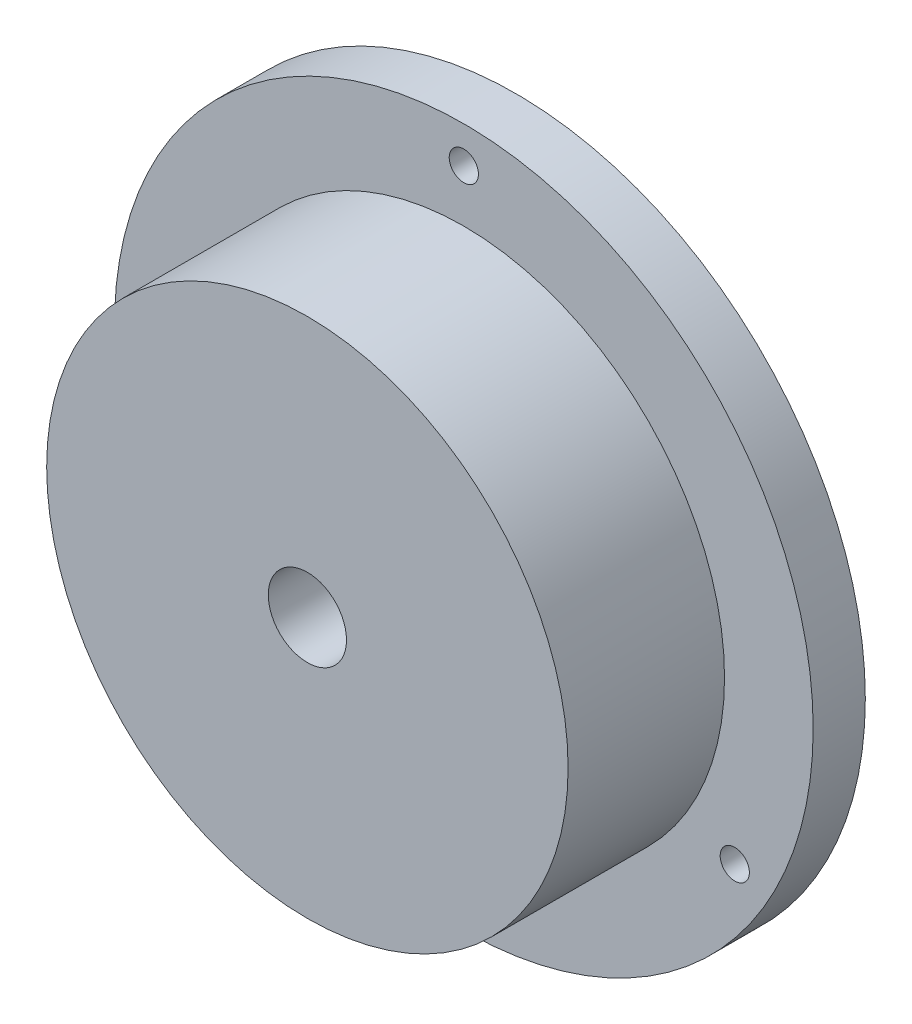
SolidWorks part; units mm, degrees
ref_plane "Front Plane" through (0, 0, 0) normal (0, 0, 1) x (1, 0, 0)
ref_plane "Top Plane" through (0, 0, 0) normal (0, 1, 0) x (1, 0, 0)
ref_plane "Right Plane" through (0, 0, 0) normal (1, 0, 0) x (0, 0, -1)
sketch "Sketch1" plane through (0, 0, 0) normal (0, 0, 1) x (1, 0, 0)
  circle A0 centre (0, 0) radius 21.2725
  dimension "D1" = 42.545
extrude "Boss-Extrude1" add sketch "Sketch1" along normal blind 3.175
sketch "Sketch2" plane through (0, 0, 3.175) normal (0, 0, 1) x (1, 0, 0)
  circle A0 centre (0, 0) radius 15.875
  dimension "D1" = 31.75
extrude "Boss-Extrude2" add sketch "Sketch2" along normal blind 9.525
hole_wizard "3/16 (0.1875) Diameter Hole1" positions "Sketch4" profile "Sketch3" hole size "3/16" standard "Ansi Inch" end condition through all
sketch "Sketch4" plane through (0, 0, 12.7) normal (0, 0, 1) x (1, 0, 0)
  point P1 (0, 0)
sketch "Sketch3" plane through (0, 0, 12.7) normal (1, 0, 0) x (0, -1, 0)
  line L0 (0, 0) -> (0, 12.7)
  line L1 (0, 12.7) -> (2.3812, 12.7)
  line L2 (2.3812, 12.7) -> (2.3812, 0)
  line L5 (2.3812, 0) -> (0, 0)
  line L11 (0, -6.35) -> (0, 107.95) construction
  dimension "Thru Hole Dia." = 4.7625
  dimension "Thru Hole Depth" = 12.7
hole_wizard "#2-56 Tapped Hole3" positions "Sketch10" profile "Sketch9" tap size "#2-56" standard "Ansi Inch" end condition through all
sketch "Sketch10" plane through (0, 0, 3.175) normal (0, 0, 1) x (1, 0, 0)
  point P1 (0, 19.05)
  dimension "D1" = 19.05
sketch "Sketch9" plane through (0, 19.05, 3.175) normal (1, 0, 0) x (0, -1, 0)
  line L0 (0, 0) -> (0, 3.175)
  line L1 (0, 3.175) -> (0.889, 3.175)
  line L2 (0.889, 3.175) -> (0.889, 0)
  line L5 (0.889, 0) -> (0, 0)
  line L11 (0, -6.35) -> (0, 107.95) construction
  dimension "Thread Major Dia." = 1.778
  dimension "Thru Tap Drill Depth" = 3.175
pattern_circular "CirPattern1" count 3 every 120 about axis through (0, 0, 0) along (0, 0, 1) of "#2-56 Tapped Hole3"
sketch "Sketch11" plane through (0, 0, 0) normal (0, 0, -1) x (-1, 0, 0)
  line L0 (0, 0) -> (0, -21.2725) construction
  circle A1 centre (0, 0) radius 21.2725 construction
ref_plane "Plane1" through (0, -21.2725, 0) normal (0, -1, 0) x (1, 0, 0)
hole_wizard "#8-32 Tapped Hole1" positions "Sketch13" profile "Sketch12" tap size "#8-32" standard "Ansi Inch"
sketch "Sketch13" plane through (0, -21.2725, 0) normal (0, -1, 0) x (1, 0, 0)
  line L0 (-21.2725, 0) -> (21.2725, 0) construction
  point P1 (0, 7.9248)
  dimension "D1" = 7.9248
sketch "Sketch12" plane through (0, -21.2725, 7.9248) normal (1, 0, 0) x (0, 0, -1)
  line L0 (0, 0) -> (0, 22.3093)
  line L1 (0, 22.3093) -> (1.7272, 21.2715)
  line L2 (1.7272, 21.2715) -> (1.7272, 0)
  line L5 (1.7272, 0) -> (0, 0)
  line L10 (0, 22.3093) -> (-1.7272, 21.2715) construction
  line L11 (0, -6.35) -> (0, 107.95) construction
  dimension "Tap Drill Dia." = 3.4544
  dimension "Tap Drill Depth" = 21.2715
  dimension "Drill Angle" = 118
sketch "Sketch14" plane through (0, 0, 0) normal (0, 0, -1) x (-1, 0, 0)
  circle A0 centre (0, 0) radius 7.9375
  dimension "D1" = 15.875
extrude "Cut-Extrude1" cut sketch "Sketch14" against normal blind 3.8862
